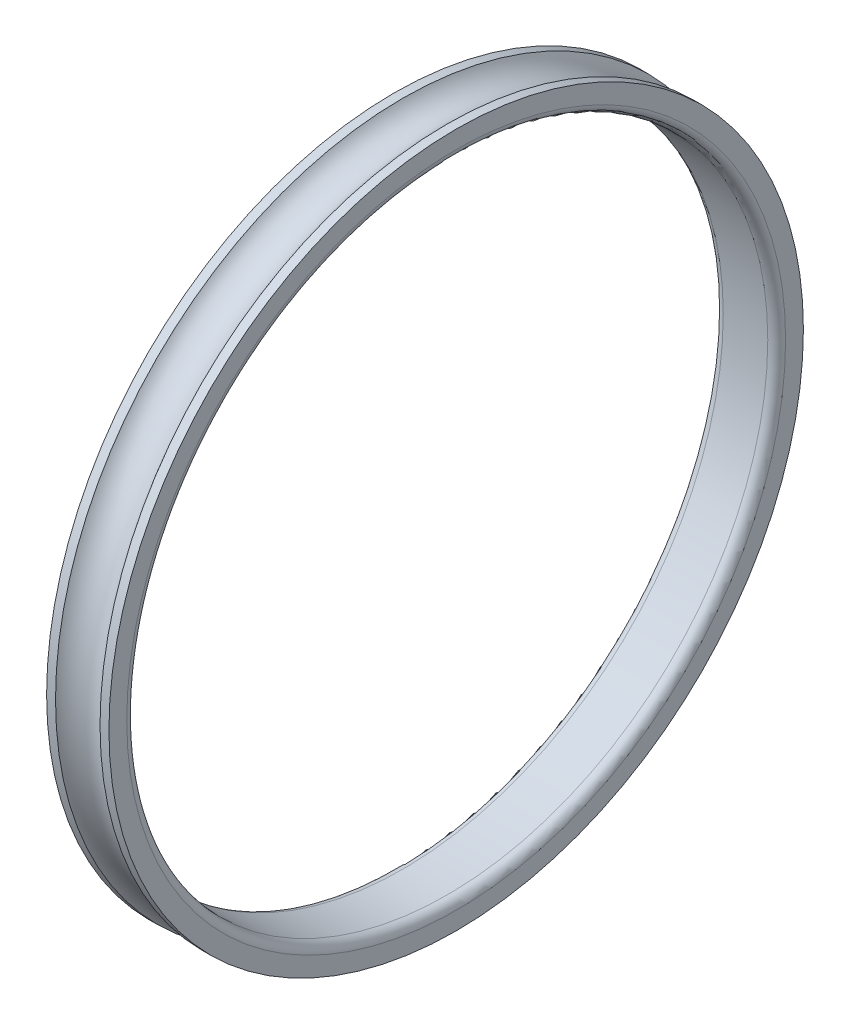
SolidWorks part; units mm, degrees
ref_plane "Front Plane" through (0, 0, 0) normal (0, 0, 1) x (1, 0, 0)
ref_plane "Top Plane" through (0, 0, 0) normal (0, 1, 0) x (1, 0, 0)
ref_plane "Right Plane" through (0, 0, 0) normal (1, 0, 0) x (0, 0, -1)
sketch "Sketch1" plane through (0, 0, 0) normal (0, 0, 1) x (1, 0, 0)
  line L5 (0, 0) -> (-277.0294, 0) construction
  line L6 (31.75, 495.3) -> (44.45, 495.3)
  line L8 (-44.45, 495.3) -> (-44.45, 469.9)
  line L9 (-44.45, 495.3) -> (-31.75, 495.3)
  line L10 (44.45, 495.3) -> (44.45, 469.9)
  line L11 (-31.75, 457.2) -> (31.75, 457.2)
  arc A7 (31.75, 495.3) -> (-31.75, 495.3) centre (0, 516.3606) cw
  arc A8 (-31.75, 457.2) -> (-44.45, 469.9) centre (-31.75, 469.9) cw
  arc A9 (31.75, 457.2) -> (44.45, 469.9) centre (31.75, 469.9) ccw
  point P18 (0, 478.2606)
  point P37 (0, 478.2606)
  dimension "D2" = 457.2
  dimension "D10" = 38.1
  dimension "D12" = 21.0606
  dimension "D8" = 38.1
  dimension "D13" = 17.9605
  dimension "D7" = 63.5
  dimension "D9" = 25.4
  dimension "D11" = 12.7
revolve "Revolve3" add sketch "Sketch1" angle 360 about L5
